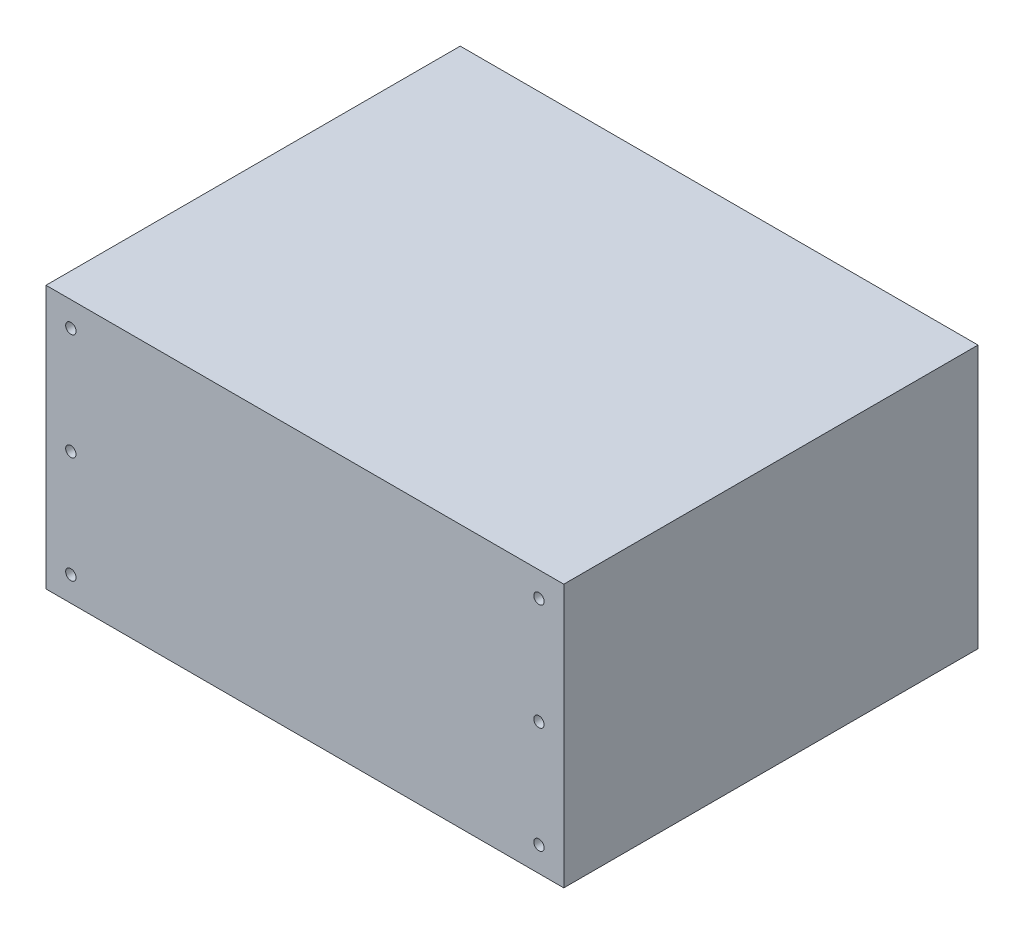
SolidWorks part; units mm, degrees
ref_plane "Front Plane" through (0, 0, 0) normal (0, 0, 1) x (1, 0, 0)
ref_plane "Top Plane" through (0, 0, 0) normal (0, 1, 0) x (1, 0, 0)
ref_plane "Right Plane" through (0, 0, 0) normal (1, 0, 0) x (0, 0, -1)
sketch "Sketch1" plane through (0, 0, 0) normal (0, 0, 1) x (1, 0, 0)
  line L1 (0, 0) -> (125, 0)
  line L2 (0, 0) -> (0, 63.5)
  line L3 (0, 63.5) -> (125, 63.5)
  line L4 (125, 0) -> (125, 63.5)
  dimension "D1" = 125
  dimension "D2" = 63.5
extrude "Boss-Extrude1" add sketch "Sketch1" along normal blind 100
sketch "Sketch2" plane through (0, 0, 100) normal (0, 0, 1) x (1, 0, 0)
  line L0 (6, 63.5) -> (6, 57.5) construction
  line L1 (125, 63.5) -> (0, 63.5) construction
  line L2 (6, 57.5) -> (0, 57.5) construction
  line L3 (0, 63.5) -> (0, 0) construction
  line L4 (119, 63.5) -> (119, 57.5)
  line L5 (119, 57.5) -> (125, 57.5)
  line L6 (125, 0) -> (125, 63.5) construction
  line L7 (0, 6) -> (6, 6) construction
  line L8 (6, 6) -> (6, 0) construction
  line L9 (0, 0) -> (125, 0) construction
  line L10 (119, 0) -> (119, 6) construction
  line L11 (119, 6) -> (125, 6) construction
  dimension "D1" = 113
  dimension "D2" = 51.5
hole_wizard "Tap Drill for M3x0.5 Tap1" positions "Sketch3" profile "Sketch4" hole size "M3x0.5" standard "ANSI Metric"
sketch "Sketch3" plane through (0, 0, 100) normal (0, 0, 1) x (1, 0, 0)
  point P0 (6, 57.5)
  point P3 (119, 57.5)
  point P6 (119, 6)
  point P9 (6, 6)
  point P12 (119, 31.75)
  point P15 (6, 31.75)
sketch "Sketch4" plane through (6, 57.5, 100) normal (1, 0, 0) x (0, -1, 0)
  line L0 (0, 0) -> (0, 5.7511)
  line L1 (0, 5.7511) -> (1.25, 5)
  line L2 (1.25, 5) -> (1.25, 0)
  line L5 (1.25, 0) -> (0, 0)
  line L10 (0, 5.7511) -> (-1.25, 5) construction
  line L11 (0, -6.35) -> (0, 107.95) construction
  dimension "Hole Dia." = 2.5
  dimension "Hole Depth" = 5
  dimension "Drill Angle" = 118
